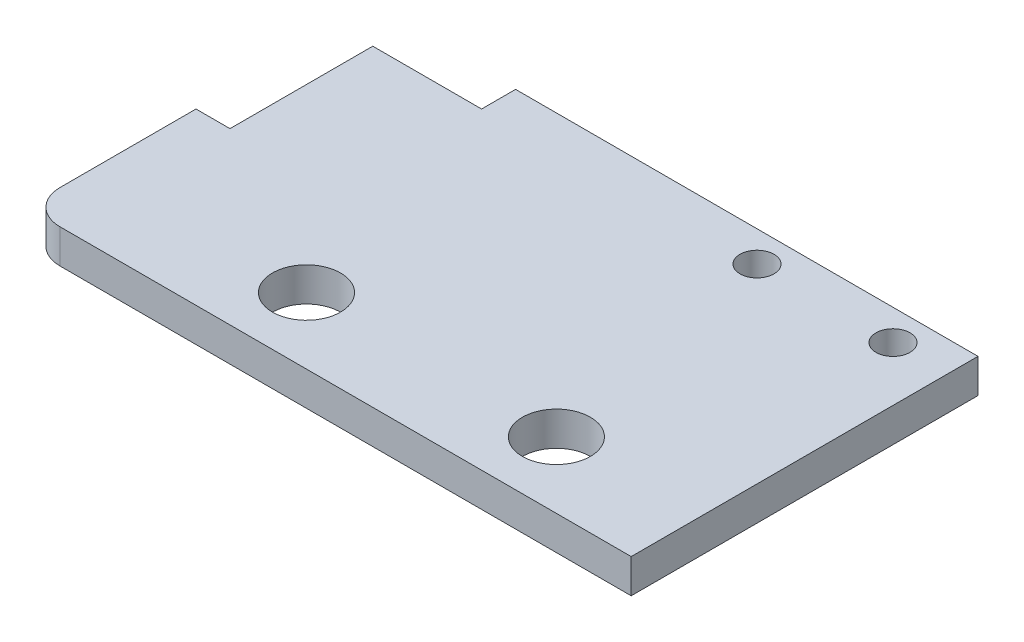
SolidWorks part; units mm, degrees
material "PP Kopolimer"
ref_plane "Front Plane" through (0, 0, 0) normal (0, 0, 1) x (1, 0, 0)
ref_plane "Top Plane" through (0, 0, 0) normal (0, 1, 0) x (1, 0, 0)
ref_plane "Right Plane" through (0, 0, 0) normal (1, 0, 0) x (0, 0, -1)
sketch "Szkic1" plane through (0, 0, 0) normal (0, 1, 0) x (1, 0, 0)
  line L1 (0, 0) -> (17.8, 0)
  line L2 (0, 0) -> (0, 5)
  line L3 (3.2, 10.2) -> (17.8, 10.2)
  line L4 (17.8, 0) -> (17.8, 10.2)
  line L5 (3.2, 10.2) -> (3.2, 9.2)
  line L6 (3.2, 9.2) -> (1, 9.2)
  line L8 (0, 5) -> (1, 5)
  line L9 (1, 5) -> (1, 9.2)
  dimension "D1" = 4.2
  dimension "D2" = 17.8
  dimension "D3" = 2.2
  dimension "D4" = 14.6
  dimension "D5" = 17.8
  dimension "D6" = 5
  dimension "D7" = 10.2
extrude "Dodanie-wyciągnięcie1" add sketch "Szkic1" along normal blind 1 contours L3 L4 L1 L2 L8 L9 L6 L5
sketch "Szkic2" plane through (0, 1, 0) normal (0, 1, 0) x (1, 0, 0)
  circle A0 centre (12.2, 9.3) radius 0.5
  circle A1 centre (16.2, 9.3) radius 0.5
  circle A2 centre (6.3, 1.95) radius 1
  circle A3 centre (13.65, 1.95) radius 1
extrude "Wytnij-wyciągnięcie1" cut sketch "Szkic2" against normal blind 1
fillet "Zaokrąglenie1" radius 1 1 edges at (0, 0.5, 0)
sketch "Szkic3" plane through (0, 1, 0) normal (0, 1, 0) x (1, 0, 0)
  line L0 (3.2, 10.2) -> (17.8, 10.2) construction
  line L1 (3.2, 9.2) -> (4.2, 9.2)
  line L2 (3.2, 9.2) -> (3.2, 10.2)
  line L3 (3.2, 10.2) -> (4.2, 10.2)
  line L4 (4.2, 9.2) -> (4.2, 10.2)
extrude "Wytnij-wyciągnięcie2" cut sketch "Szkic3" against normal blind 10
